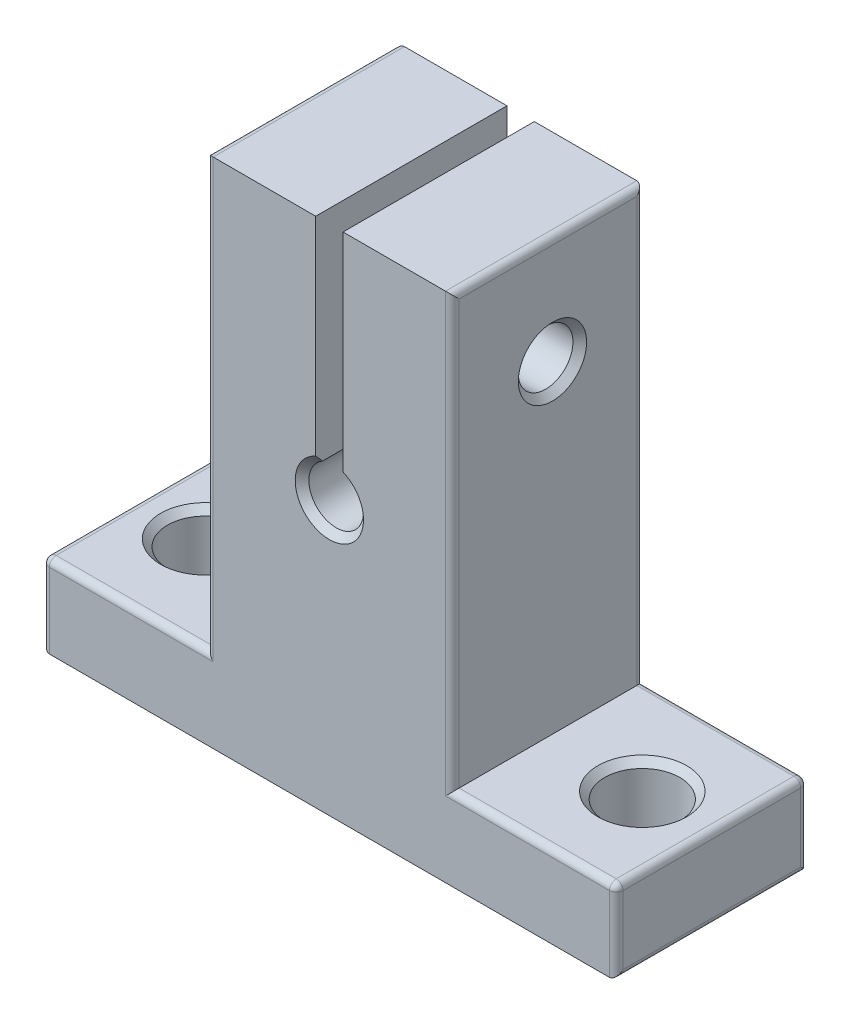
SolidWorks part; units mm, degrees
material "1060 Alloy"
ref_plane "Front Plane" through (0, 0, 0) normal (0, 0, 1) x (1, 0, 0)
ref_plane "Top Plane" through (0, 0, 0) normal (0, 1, 0) x (1, 0, 0)
ref_plane "Right Plane" through (0, 0, 0) normal (1, 0, 0) x (0, 0, -1)
sketch "Sketch1" plane through (0, 0, 0) normal (0, 0, 1) x (1, 0, 0)
  line L0 (0, 0) -> (-50000, 0) construction
  line L1 (0, 0) -> (0, 50000) construction
  line L2 (-21, -3) -> (-21, 3)
  line L3 (-21, 3) -> (-9, 3)
  line L4 (-9, 3) -> (-9, 34.5)
  line L5 (-9, 34.5) -> (-1, 34.5)
  line L6 (9, 34.5) -> (9, 3)
  line L7 (9, 3) -> (21, 3)
  line L8 (21, 3) -> (21, -3)
  line L9 (21, -3) -> (-21, -3)
  line L10 (16, -3) -> (16, 3) construction
  line L11 (-16, -3) -> (-16, 3) construction
  line L12 (-1, 34.5) -> (-1, 18.7321)
  line L13 (1, 34.5) -> (1, 18.7321)
  line L14 (1, 34.5) -> (9, 34.5)
  arc A0 (-1, 18.7321) -> (1, 18.7321) centre (0, 17) ccw
  point P8 (-21, 0)
  point P15 (0, -3)
  point P21 (16, 0)
  dimension "Shaft Diameter" = 4
  dimension "W" = 42
  dimension "P" = 18
  dimension "F" = 37.5
  dimension "G" = 6
  dimension "B" = 32
  dimension "D1" = 2
  dimension "h" = 20
extrude "Boss-Extrude1" add sketch "Sketch1" along normal mid plane 14
sketch "Sketch2" plane through (0, 3, 0) normal (0, 1, 0) x (1, 0, 0)
  line L0 (0, 0) -> (50000, 0) construction
  line L1 (0.3141, 0) -> (-49999.6859, 0) construction
  line L2 (-0.0955, 2.4842) -> (-0.0955, 50002.4842) construction
  circle A0 centre (15.9045, 0) radius 2.75
  circle A1 centre (-16.0955, 0) radius 2.75
  dimension "B" = 32
  dimension "S" = 5.5
extrude "Cut-Extrude1" cut sketch "Sketch2" against normal through all
sketch "Sketch5" plane through (-1, 0, 0) normal (1, 0, 0) x (0, 0, -1)
  line L0 (-7, 26.616) -> (7, 26.616) construction
  line L1 (7, 18.7321) -> (7, 34.5) construction
  line L2 (0, 34.5) -> (0, 18.7321) construction
  line L3 (-7, 34.5) -> (7, 34.5) construction
  line L4 (-7, 18.7321) -> (7, 18.7321) construction
  line L5 (-7, 18.7321) -> (-7, 34.5) construction
  circle A0 centre (0.3307, 26.616) radius 2
  dimension "Clamping bold" = 4
extrude "Cut-Extrude2" cut sketch "Sketch5" against normal through all both and the other way through all
chamfer "Chamfer2" distance 0.5 angle 45 6 edges at (0, 15, -7) (0, 15, 7) (-9, 26.616, -2.3307) (-13.3455, 3, 0) (9, 26.616, 1.6693) (13.1545, 3, 0)
fillet "Fillet2" radius 0.5 18 edges at (21, -3, 0) (21, 0, 7) (21, 3, 0) (21, 0, -7) (-21, 3, 0) (-21, 0, 7) (-21, -3, 0) (-21, 0, -7) (-15, 3, -7) (-15, 3, 7) (-9, 18.75, 7) (-9, 34.5, 0) (-9, 18.75, -7) (9, 18.75, -7) (9, 18.75, 7) (15, 3, 7) (15, 3, -7) (9, 34.5, 0)
equation "\"W\"= \"W@Sketch1\"'Width"
equation "\"B\"= \"B@Sketch1\"'between hold"
equation "\"F\"= \"F@Sketch1\"'Hight"
equation "\"P\"= \"P@Sketch1\""
equation "\"G\"= \"G@Sketch1\""
equation "\"Shaft diameter\"= \"Shaft Diameter@Sketch1\""
equation "\"S\"= 5.5'M5"
equation "\"Clamping bold\"= 4'M4"
equation "\"h\"= \"h@Sketch1\""
